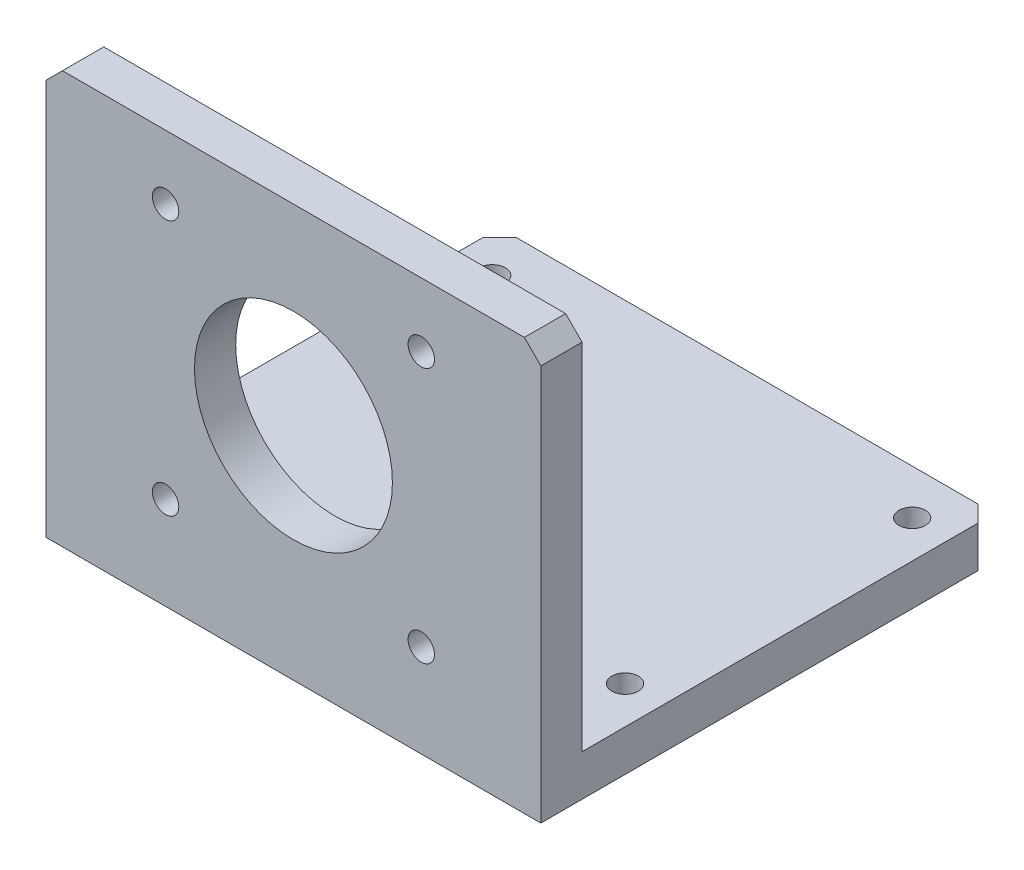
SolidWorks part; units mm, degrees
ref_plane "前视基准面" through (0, 0, 0) normal (0, 0, 1) x (1, 0, 0)
ref_plane "上视基准面" through (0, 0, 0) normal (0, 1, 0) x (1, 0, 0)
ref_plane "右视基准面" through (0, 0, 0) normal (1, 0, 0) x (0, 0, -1)
other "Configuration Table"
sketch "草图1" plane through (0, 0, 0) normal (1, 0, 0) x (0, 0, -1)
  line L0 (0, 0) -> (0, 50)
  line L1 (0, 50) -> (5, 50)
  line L2 (5, 50) -> (5, 5)
  line L3 (5, 5) -> (60, 5)
  line L4 (0, 0) -> (60, 0)
  line L5 (60, 0) -> (60, 5)
  dimension "D1" = 45
  dimension "D2" = 5
  dimension "D3" = 5
  dimension "D4" = 60
extrude "凸台-拉伸1" add sketch "草图1" along normal blind 60
sketch "草图4" plane through (0, 5, 0) normal (0, 1, 0) x (1, 0, 0)
  line L0 (60, 5) -> (60, 0) construction
  line L1 (0, 60) -> (60, 60)
  line L2 (0, 60) -> (0, 5)
  line L3 (0, 5) -> (60, 5)
  line L4 (60, 60) -> (60, 5)
  line L5 (60, 5) -> (0, 5) construction
hole_wizard "孔2" positions "草图6" profile "草图7" legacy end condition through all
sketch "草图6" plane through (0, 0, 0) normal (0, 0, 1) x (1, 0, 0)
  point P0 (30, 26.75)
sketch "草图7" plane through (30, 26.75, 0) normal (1, 0, 0) x (0, -1, 0)
  line L0 (0, 0) -> (0, 60)
  line L1 (0, 60) -> (12, 60)
  line L2 (12, 60) -> (12, 0)
  line L3 (12, 0) -> (0, 0)
  line L4 (0, 110) -> (0, -10) construction
  dimension "直径" = 24
  dimension "深度" = 60
hole_wizard "孔3" positions "草图10" profile "草图11" legacy end condition through all
sketch "草图10" plane through (0, 0, 0) normal (0, 0, 1) x (1, 0, 0)
  point P0 (14.5, 42.25)
  point P3 (45.5, 42.25)
  point P6 (45.5, 11.25)
  point P9 (14.5, 11.25)
sketch "草图11" plane through (14.5, 42.25, 0) normal (1, 0, 0) x (0, -1, 0)
  line L0 (0, 0) -> (0, 60)
  line L1 (0, 60) -> (1.6, 60)
  line L2 (1.6, 60) -> (1.6, 0)
  line L3 (1.6, 0) -> (0, 0)
  line L4 (0, 110) -> (0, -10) construction
  dimension "直径" = 3.2
  dimension "深度" = 60
hole_wizard "孔4" positions "草图12" profile "草图13" legacy end condition through all
sketch "草图12" plane through (0, 5, 0) normal (0, 1, 0) x (1, 0, 0)
  point P0 (55.4593, 14.749)
  point P2 (55.4593, 49.5575)
  point P13 (4.5407, 14.749)
  point P14 (4.5407, 49.5575)
sketch "草图13" plane through (55.4593, 5, -14.749) normal (1, 0, 0) x (0, 0, 1)
  line L0 (0, 0) -> (0, 5)
  line L1 (0, 5) -> (1.6, 5)
  line L2 (1.6, 5) -> (1.6, 0)
  line L3 (1.6, 0) -> (0, 0)
  line L4 (0, 110) -> (0, -10) construction
  dimension "直径" = 3.2
  dimension "深度" = 5
sketch "草图14" plane through (0, 0, -60) normal (0, 0, -1) x (-1, 0, 0)
  line L1 (-60, 5) -> (0, 5)
  line L2 (-60, 5) -> (-60, 0)
  line L3 (-60, 0) -> (0, 0)
  line L4 (0, 5) -> (0, 0)
extrude "切除-拉伸1" cut sketch "草图14" against normal blind 5
chamfer "倒角1" distance 2 angle 45 4 edges at (60, 2.5, -55) (0, 2.5, -55) (0, 50, -2.5) (60, 50, -2.5)
